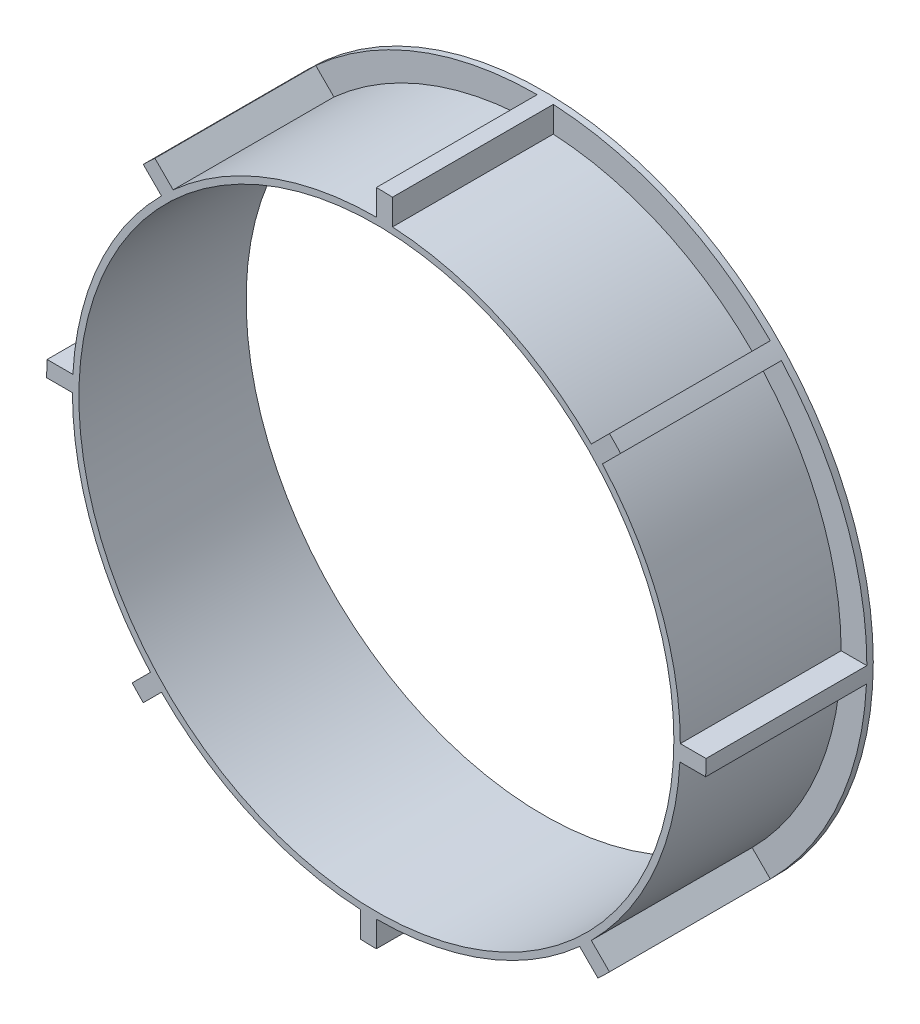
SolidWorks part; units mm, degrees
ref_plane "Front Plane" through (0, 0, 0) normal (0, 0, 1) x (1, 0, 0)
ref_plane "Top Plane" through (0, 0, 0) normal (0, 1, 0) x (1, 0, 0)
ref_plane "Right Plane" through (0, 0, 0) normal (1, 0, 0) x (0, 0, -1)
sketch "Sketch1" plane through (0, 0, 0) normal (0, 0, 1) x (1, 0, 0)
  circle A0 centre (0, 0) radius 92.5
  circle A1 centre (0, 0) radius 102.5
  dimension "D1" = 185
  dimension "D2" = 10
extrude "Boss-Extrude1" add sketch "Sketch1" along normal blind 2
sketch "Sketch2" plane through (0, 0, 2) normal (0, 0, 1) x (1, 0, 0)
  circle A0 centre (0, 0) radius 92.5 construction
  circle A1 centre (0, 0) radius 92.5
  circle A3 centre (0, 0) radius 94.5
  circle A4 centre (0, 0) radius 92.5
  circle A5 centre (0, 0) radius 92.5
  circle M4 centre (0, 0) radius 92.5
  dimension "D1" = 10
  dimension "D2" = 2
extrude "Boss-Extrude2" add sketch "Sketch2" along normal blind 50 contours A3 M4
sketch "Sketch3" plane through (0, 0, 2) normal (0, 0, 1) x (1, 0, 0)
  line L0 (0, 94.5) -> (0, 102.5)
  line L1 (5, 94.3676) -> (5, 102.378)
  circle A0 centre (0, 0) radius 94.5 construction
  circle A1 centre (0, 0) radius 94.5
  circle A2 centre (0, 0) radius 102.5 construction
  circle A3 centre (0, 0) radius 102.5
  circle M5 centre (0, 0) radius 94.5
  circle M6 centre (0, 0) radius 102.5
  dimension "D1" = 5
extrude "Boss-Extrude3" add sketch "Sketch3" along normal blind 50 contours L1 L0 M5 M6
pattern_circular "CirPattern1" count 8 over 360 about axis through (0, 0, 0) along (0, 0, 1) of "Boss-Extrude3"
